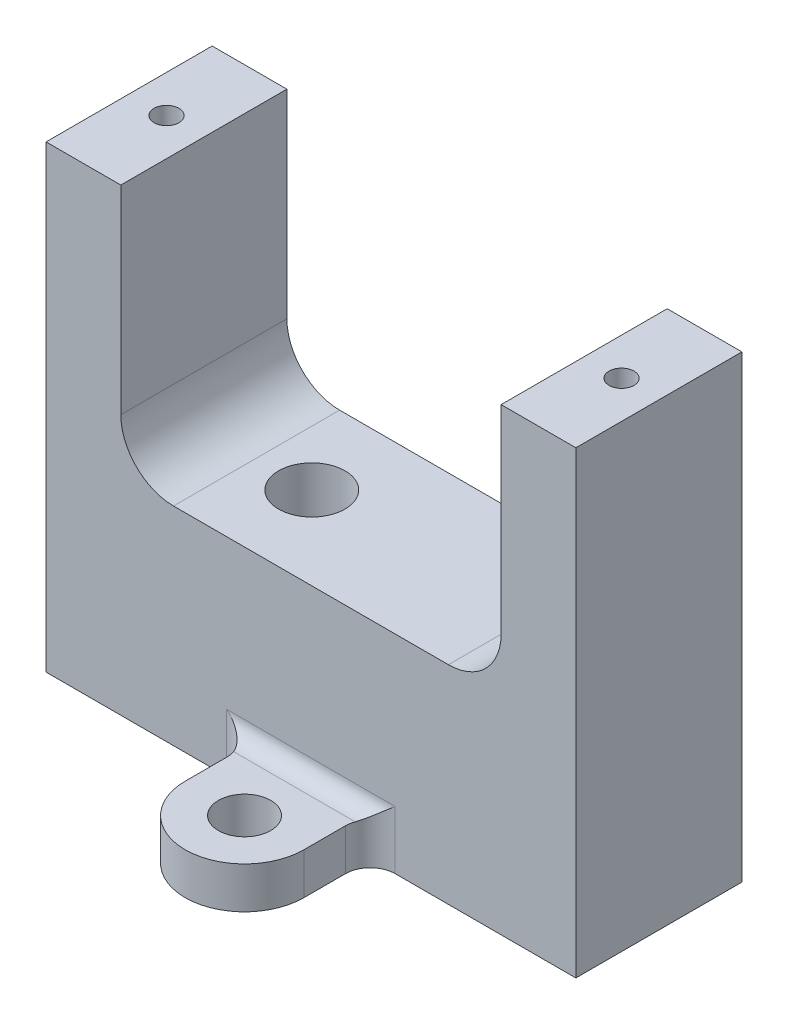
SolidWorks part; units mm, degrees
ref_plane "Front Plane" through (0, 0, 0) normal (0, 0, 1) x (1, 0, 0)
ref_plane "Top Plane" through (0, 0, 0) normal (0, 1, 0) x (1, 0, 0)
ref_plane "Right Plane" through (0, 0, 0) normal (1, 0, 0) x (0, 0, -1)
sketch "Sketch1" plane through (0, 0, 0) normal (0, 1, 0) x (1, 0, 0)
  line L0 (-15.95, 5) -> (-11.45, -5) construction
  line L1 (-15.95, 5) -> (-11.45, 5)
  line L2 (-15.95, 5) -> (-15.95, -5)
  line L3 (-15.95, -5) -> (-11.45, -5)
  line L4 (-11.45, 5) -> (-11.45, -5)
  line L5 (0, 0) -> (0, -5) construction
  line L6 (0, -5) -> (-11.45, -5) construction
  line L7 (15.95, 5) -> (11.45, -5) construction
  line L8 (11.45, 5) -> (11.45, -5)
  line L9 (15.95, -5) -> (11.45, -5)
  line L10 (15.95, 5) -> (15.95, -5)
  line L11 (15.95, 5) -> (11.45, 5)
  circle A0 centre (-13.7, 0) radius 0.75 construction
  circle A2 centre (13.7, 0) radius 0.75 construction
  dimension "D1" = 1.5
  dimension "D2" = 13.7
  dimension "D3" = 10
  dimension "D4" = 4.5
extrude "Boss-Extrude1" add sketch "Sketch1" against normal blind 15.15
hole_wizard "Ø1.5mm Dowel Hole1" positions "Sketch3" profile "Sketch4" hole size "Ø1.5" standard "ANSI Metric"
sketch "Sketch3" plane through (0, 0, 0) normal (0, 1, 0) x (1, 0, 0)
  line L0 (15.95, 5) -> (11.45, -5) construction
  point P0 (-13.7, 0)
  point P3 (13.7, 0)
sketch "Sketch4" plane through (-13.7, 0, 0) normal (1, 0, 0) x (0, 0, 1)
  line L0 (0, 0) -> (0, 12)
  line L1 (0, 12) -> (0.75, 11.5494)
  line L2 (0.75, 11.5494) -> (0.75, 0)
  line L5 (0.75, 0) -> (0, 0)
  line L10 (0, 12) -> (-0.75, 11.5494) construction
  line L11 (0, -6.35) -> (0, 107.95) construction
  dimension "Hole Dia." = 1.5
  dimension "Hole Depth" = 12
  dimension "Drill Angle" = 118
sketch "Sketch5" plane through (0, -15.15, 0) normal (0, -1, 0) x (1, 0, 0)
  line L4 (-15.95, 5) -> (-15.95, -5)
  line L5 (-15.95, -5) -> (-11.45, -5)
  line L6 (-11.45, -5) -> (-11.45, 5)
  line L7 (-11.45, 5) -> (-15.95, 5)
  line L8 (-15.95, 5) -> (-15.95, -5)
  line L9 (-15.95, -5) -> (15.95, -5)
  line L11 (15.95, 5) -> (-15.95, 5)
  line L12 (11.45, -5) -> (15.95, -5)
  line L13 (15.95, -5) -> (15.95, 5)
  line L14 (15.95, 5) -> (11.45, 5)
  line L15 (11.45, 5) -> (11.45, -5)
  line L17 (15.95, -5) -> (15.95, 5)
  circle A0 centre (-4.95, 0) radius 2
  circle A1 centre (-13.7, 0) radius 0.75 construction
  point P4 (0, 0)
  dimension "D1" = 4
  dimension "D2" = 8.75
  dimension "D3" = 0
  dimension "D4" = 0
extrude "Boss-Extrude2" add sketch "Sketch5" along normal blind 12.5
fillet "Fillet1" radius 3.175 2 edges at (11.45, -15.15, 0) (-11.45, -15.15, 0)
sketch "Sketch6" plane through (-15.95, 0, 0) normal (-1, 0, 0) x (0, 0, 1)
  line L0 (5, -15.15) -> (-5, -15.15) construction
  line L1 (5, -15.15) -> (-5, -15.15) construction
  circle A0 centre (-1.2, -20.65) radius 2
  point P4 (0, 0)
  point P7 (0, 0)
  point P8 (-1.2999, -20.65)
  dimension "D1" = 4
  dimension "D2" = 5.5
  dimension "D3" = 1.2
extrude "Cut-Extrude1" cut sketch "Sketch6" against normal blind 15.4
sketch "Sketch7" plane through (0, -27.65, 0) normal (0, -1, 0) x (1, 0, 0)
  line L0 (-15.95, -5) -> (15.95, -5) construction
  line L1 (15.95, 5) -> (-15.95, 5) construction
  line L2 (-3.575, -5) -> (3.575, -5)
  line L3 (3.575, 5) -> (-3.575, 5)
  line L4 (0, 0) -> (15.95, 0) construction
  line L5 (15.95, -5) -> (15.95, 5) construction
  line L6 (-3.575, 9) -> (-3.575, 5)
  line L7 (3.575, 9) -> (3.575, 5)
  line L8 (3.575, -5) -> (-3.575, -5)
  line L9 (3.575, -9) -> (3.575, -5)
  line L10 (-3.575, -9) -> (-3.575, -5)
  circle A0 centre (0, 9) radius 1.575
  arc A1 (3.575, 9) -> (-3.575, 9) centre (0, 9) ccw
  circle A2 centre (0, 9) radius 3.575 construction
  circle A3 centre (0, -9) radius 1.575
  arc A4 (3.575, -9) -> (-3.575, -9) centre (0, -9) cw
  point P17 (0, 0)
  line M6 (-15.95, -5) -> (15.95, -5)
  dimension "D1" = 3.15
  dimension "D2" = 2
  dimension "D3" = 4
extrude "Boss-Extrude3" add sketch "Sketch7" against normal blind 2.5 contours L7 A1 L6 L3 A0 | A4 L9 L10 A3 M6
fillet "Fillet3" radius 1.5 4 edges at (3.575, -26.4, -5) (-3.575, -26.4, -5) (-3.575, -26.4, 5) (3.575, -26.4, 5)
fillet "Fillet4" radius 1 2 edges at (0, -25.15, 5) (0, -25.15, -5)
